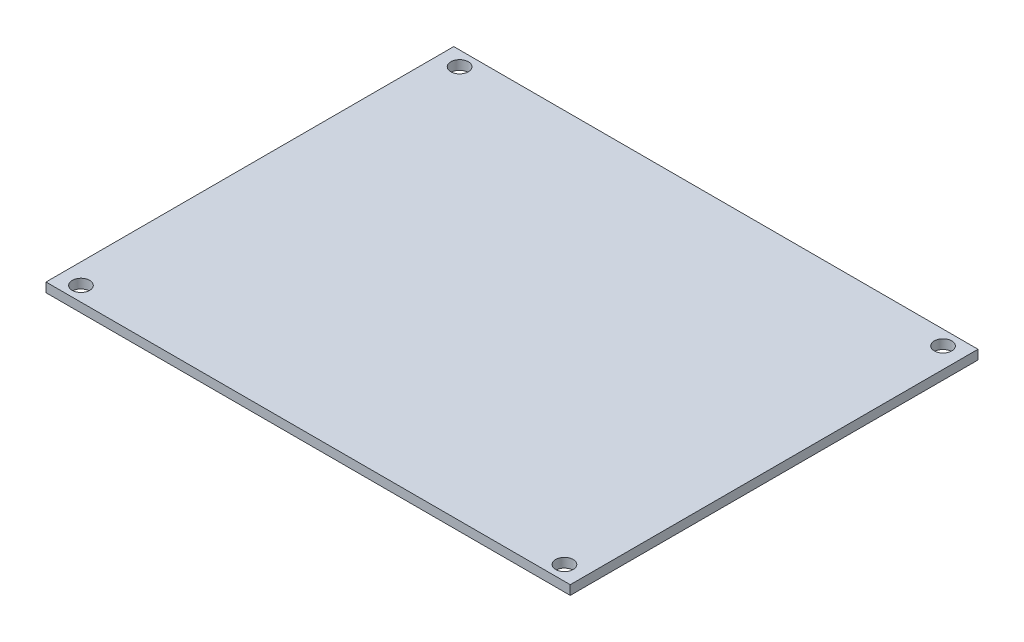
SolidWorks part; units mm, degrees
ref_plane "Front Plane" through (0, 0, 0) normal (0, 0, 1) x (1, 0, 0)
ref_plane "Top Plane" through (0, 0, 0) normal (0, 1, 0) x (1, 0, 0)
ref_plane "Right Plane" through (0, 0, 0) normal (1, 0, 0) x (0, 0, -1)
sketch "Sketch1" plane through (0, 0, 0) normal (0, 1, 0) x (1, 0, 0)
  line L1 (-45, -35) -> (45, -35)
  line L2 (-45, -35) -> (-45, 35)
  line L3 (-45, 35) -> (45, 35)
  line L4 (45, -35) -> (45, 35)
  line L5 (-45, -35) -> (45, 35) construction
  line L6 (-45, 35) -> (45, -35) construction
  point P0 (0, 0)
  dimension "D1" = 90
  dimension "D2" = 70
extrude "Boss-Extrude1" add sketch "Sketch1" along normal blind 1.6
sketch "Sketch2" plane through (0, 1.6, 0) normal (0, 1, 0) x (1, 0, 0)
  line L1 (-45, 35) -> (-45, -35) construction
  line L3 (45, -35) -> (45, 35) construction
  circle A0 centre (-41.5, 32.5) radius 1.5
  circle A1 centre (41.5, 32.5) radius 1.5
  circle A2 centre (41.5, -32.5) radius 1.5
  circle A3 centre (-41.5, -32.5) radius 1.5
  dimension "D1" = 3
  dimension "D3" = 3.5
  dimension "D7" = 3.5
  dimension "D2" = 32.5
  dimension "D6" = 32.5
  dimension "D4" = 2
  dimension "D5" = 2
extrude "Cut-Extrude1" cut sketch "Sketch2" against normal blind 1.6
equation "\"D6@Sketch2\"=\"D2@Sketch2\""
